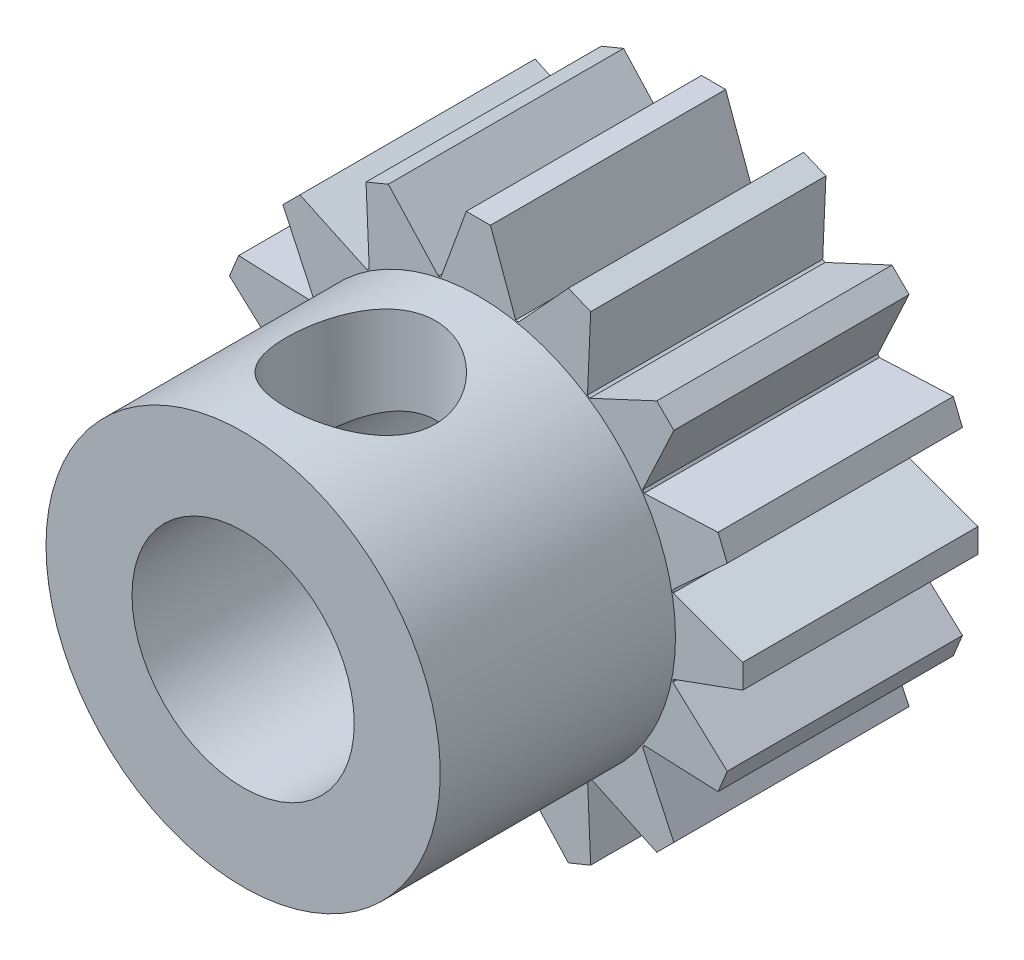
SolidWorks part; units mm, degrees
ref_plane "Front Plane" through (0, 0, 0) normal (0, 0, 1) x (1, 0, 0)
ref_plane "Top Plane" through (0, 0, 0) normal (0, 1, 0) x (1, 0, 0)
ref_plane "Right Plane" through (0, 0, 0) normal (1, 0, 0) x (0, 0, -1)
ref_plane "Plane1" through (0, 0, 3.175) normal (0, 0, 1) x (1, 0, 0)
sketch "Sketch1" plane through (0, 0, 3.175) normal (0, 0, 1) x (1, 0, 0)
  line L0 (2.9452, 4.4757) -> (3.0322, 6.4695)
  line L1 (3.0322, 6.4695) -> (2.4305, 6.7187)
  line L2 (2.4305, 6.7187) -> (1.0823, 5.2474)
  line L3 (1.0082, 5.2621) -> (0.3257, 7.1374)
  line L4 (0.3257, 7.1374) -> (-0.3257, 7.1374)
  line L5 (-0.3257, 7.1374) -> (-1.0082, 5.2621)
  line L6 (-1.0823, 5.2474) -> (-2.4305, 6.7187)
  line L7 (-2.4305, 6.7187) -> (-3.0322, 6.4695)
  line L8 (-3.0322, 6.4695) -> (-2.9452, 4.4757)
  line L9 (-3.008, 4.4338) -> (-4.8166, 5.2772)
  line L10 (-4.8166, 5.2772) -> (-5.2772, 4.8166)
  line L11 (-5.2772, 4.8166) -> (-4.4338, 3.008)
  line L12 (-4.4757, 2.9452) -> (-6.4695, 3.0322)
  line L13 (-6.4695, 3.0322) -> (-6.7187, 2.4305)
  line L14 (-6.7187, 2.4305) -> (-5.2474, 1.0823)
  line L15 (-5.2621, 1.0082) -> (-7.1374, 0.3257)
  line L16 (-7.1374, 0.3257) -> (-7.1374, -0.3257)
  line L17 (-7.1374, -0.3257) -> (-5.2621, -1.0082)
  line L18 (-5.2474, -1.0823) -> (-6.7187, -2.4305)
  line L19 (-6.7187, -2.4305) -> (-6.4695, -3.0322)
  line L20 (-6.4695, -3.0322) -> (-4.4757, -2.9452)
  line L21 (-4.4338, -3.008) -> (-5.2772, -4.8166)
  line L22 (-5.2772, -4.8166) -> (-4.8166, -5.2772)
  line L23 (-4.8166, -5.2772) -> (-3.008, -4.4338)
  line L24 (-2.9452, -4.4757) -> (-3.0322, -6.4695)
  line L25 (-3.0322, -6.4695) -> (-2.4305, -6.7187)
  line L26 (-2.4305, -6.7187) -> (-1.0823, -5.2474)
  line L27 (-1.0082, -5.2621) -> (-0.3257, -7.1374)
  line L28 (-0.3257, -7.1374) -> (0.3257, -7.1374)
  line L29 (0.3257, -7.1374) -> (1.0082, -5.2621)
  line L30 (1.0823, -5.2474) -> (2.4305, -6.7187)
  line L31 (2.4305, -6.7187) -> (3.0322, -6.4695)
  line L32 (3.0322, -6.4695) -> (2.9452, -4.4757)
  line L33 (3.008, -4.4338) -> (4.8166, -5.2772)
  line L34 (4.8166, -5.2772) -> (5.2772, -4.8166)
  line L35 (5.2772, -4.8166) -> (4.4338, -3.008)
  line L36 (4.4757, -2.9452) -> (6.4695, -3.0322)
  line L37 (6.4695, -3.0322) -> (6.7187, -2.4305)
  line L38 (6.7187, -2.4305) -> (5.2474, -1.0823)
  line L39 (5.2621, -1.0082) -> (7.1374, -0.3257)
  line L40 (7.1374, -0.3257) -> (7.1374, 0.3257)
  line L41 (7.1374, 0.3257) -> (5.2621, 1.0082)
  line L42 (5.2474, 1.0823) -> (6.7187, 2.4305)
  line L43 (6.7187, 2.4305) -> (6.4695, 3.0322)
  line L44 (6.4695, 3.0322) -> (4.4757, 2.9452)
  line L45 (4.4338, 3.008) -> (5.2772, 4.8166)
  line L46 (5.2772, 4.8166) -> (4.8166, 5.2772)
  line L47 (4.8166, 5.2772) -> (3.008, 4.4338)
  arc A0 (1.0823, 5.2474) -> (1.0082, 5.2621) centre (0, 0) ccw
  arc A1 (-1.0082, 5.2621) -> (-1.0823, 5.2474) centre (0, 0) ccw
  arc A2 (-2.9452, 4.4757) -> (-3.008, 4.4338) centre (0, 0) ccw
  arc A3 (-4.4338, 3.008) -> (-4.4757, 2.9452) centre (0, 0) ccw
  arc A4 (-5.2474, 1.0823) -> (-5.2621, 1.0082) centre (0, 0) ccw
  arc A5 (-5.2621, -1.0082) -> (-5.2474, -1.0823) centre (0, 0) ccw
  arc A6 (-4.4757, -2.9452) -> (-4.4338, -3.008) centre (0, 0) ccw
  arc A7 (-3.008, -4.4338) -> (-2.9452, -4.4757) centre (0, 0) ccw
  arc A8 (-1.0823, -5.2474) -> (-1.0082, -5.2621) centre (0, 0) ccw
  arc A9 (1.0082, -5.2621) -> (1.0823, -5.2474) centre (0, 0) ccw
  arc A10 (2.9452, -4.4757) -> (3.008, -4.4338) centre (0, 0) ccw
  arc A11 (4.4338, -3.008) -> (4.4757, -2.9452) centre (0, 0) ccw
  arc A12 (5.2474, -1.0823) -> (5.2621, -1.0082) centre (0, 0) ccw
  arc A13 (5.2621, 1.0082) -> (5.2474, 1.0823) centre (0, 0) ccw
  arc A14 (4.4757, 2.9452) -> (4.4338, 3.008) centre (0, 0) ccw
  arc A15 (3.008, 4.4338) -> (2.9452, 4.4757) centre (0, 0) ccw
extrude "Boss-Extrude1" add sketch "Sketch1" against normal blind 6.35
ref_plane "Plane2" through (0, 0, 0) normal (0, -1, 0) x (1, 0, 0)
sketch "Sketch2" plane through (0, 0, 0) normal (0, -1, 0) x (1, 0, 0)
  line L0 (5.3213, 9.525) -> (0, 9.525)
  line L1 (0, 9.525) -> (0, 3.175)
  line L2 (0, 3.175) -> (5.3213, 3.175)
  line L3 (5.3213, 3.175) -> (5.3213, 9.525)
  line L4 (0, 9.525) -> (0, 3.175) construction
revolve "Revolve1" add sketch "Sketch2" angle 360 about L4
hole_wizard "#12 Clearance Hole1" positions "Sketch4" profile "Sketch3" hole size "#12" standard "ANSI Inch"
sketch "Sketch4" plane through (0, 0, 9.525) normal (0, 0, 1) x (1, 0, 0)
  point P0 (0, 0)
sketch "Sketch3" plane through (0, 0, 9.525) normal (1, 0, 0) x (0, -1, 0)
  line L0 (0, 0) -> (0, 12.7)
  line L1 (0, 12.7) -> (3, 12.7)
  line L2 (3, 12.7) -> (3, 0)
  line L5 (3, 0) -> (0, 0)
  line L11 (0, -6.35) -> (0, 107.95) construction
  dimension "Thru Hole Dia." = 6
  dimension "Thru Hole Depth" = 12.7
hole_wizard "#21 (0.159) Diameter Hole1" positions "3DSketch1" profile "Sketch5" hole size "#21" standard "ANSI Inch"
sketch3d "3DSketch1"
  point P0 (0, 5.3213, 6.35)
sketch "Sketch5" plane through (0, 5.3213, 6.35) normal (1, 0, 0) x (0, 0, 1)
  line L0 (0, 0) -> (0, 2.3213)
  line L1 (0, 2.3213) -> (2.0193, 2.3213)
  line L2 (2.0193, 2.3213) -> (2.0193, 0)
  line L5 (2.0193, 0) -> (0, 0)
  line L11 (0, -6.35) -> (0, 107.95) construction
  dimension "Thru Hole Dia." = 4.0386
  dimension "Thru Hole Depth" = 2.3213
